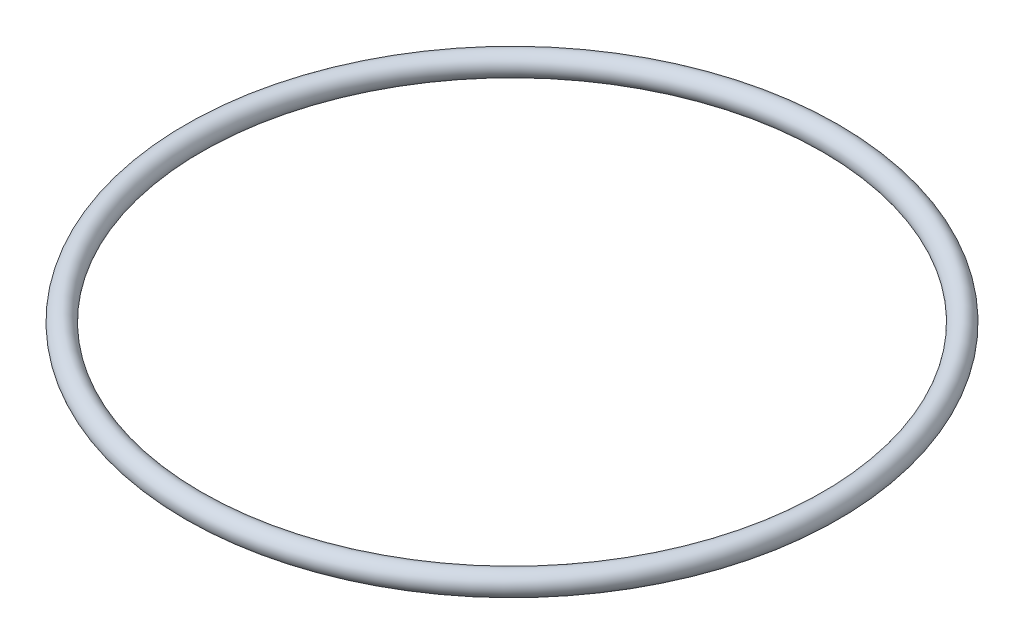
SolidWorks part; units mm, degrees
ref_plane "Front Plane" through (0, 0, 0) normal (0, 0, 1) x (1, 0, 0)
ref_plane "Top Plane" through (0, 0, 0) normal (0, 1, 0) x (1, 0, 0)
ref_plane "Right Plane" through (0, 0, 0) normal (1, 0, 0) x (0, 0, -1)
sketch "Sketch1" plane through (0, 0, 0) normal (1, 0, 0) x (0, 0, -1)
  line L0 (0, -6.8434) -> (0, 8.6434) construction
  circle A0 centre (-25.7, 0) radius 0.9
  dimension "D1" = 1.8
  dimension "D2" = 25.7
revolve "Revolve1" add sketch "Sketch1" angle 360 about L0
